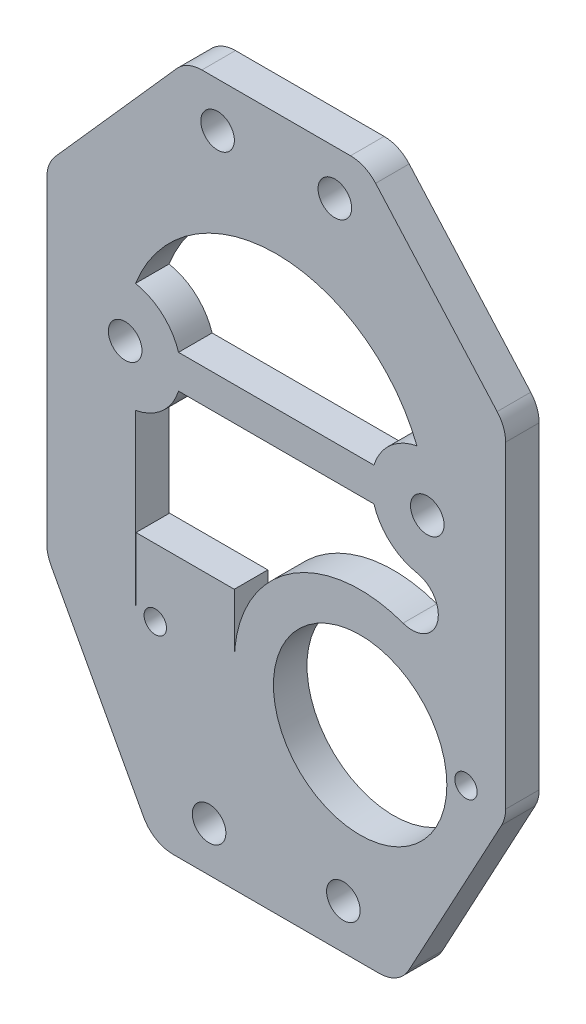
SolidWorks part; units mm, degrees
ref_plane "Front Plane" through (0, 0, 0) normal (0, 0, 1) x (1, 0, 0)
ref_plane "Top Plane" through (0, 0, 0) normal (0, 1, 0) x (1, 0, 0)
ref_plane "Right Plane" through (0, 0, 0) normal (1, 0, 0) x (0, 0, -1)
sketch "Sketch1" plane through (0, 0, 0) normal (0, 0, 1) x (1, 0, 0)
  line L0 (0, 0) -> (0, 62) construction
  line L1 (7.9898, 62) -> (-7.9898, 62)
  line L2 (-7.9898, 62) -> (-20.5, 47.8997)
  line L3 (-20.5, 47.8997) -> (-20.5, 17.5997)
  line L4 (-20.5, 17.5997) -> (-11, 0)
  line L5 (-11, 0) -> (0, 0)
  line L6 (20.5, 17.5997) -> (11, 0)
  line L7 (20.5, 47.8997) -> (20.5, 17.5997)
  line L8 (7.9898, 62) -> (20.5, 47.8997)
  line L9 (7.5, 17.5997) -> (20.5, 17.5997) construction
  line L10 (-13.5, 37.5997) -> (13.5, 37.5997) construction
  line L11 (13.5, 37.5997) -> (11.3388, 28.1745) construction
  line L12 (8.7303, 36.0997) -> (-8.7303, 36.0997)
  line L13 (8.7303, 36.0997) -> (8.7303, 39.0997) construction
  line L14 (8.7303, 39.0997) -> (-8.7303, 39.0997)
  line L15 (-8.7303, 36.0997) -> (-8.7303, 39.0997) construction
  line L16 (8.7303, 36.0997) -> (-8.7303, 39.0997) construction
  line L17 (8.7303, 39.0997) -> (-8.7303, 36.0997) construction
  line L18 (-12.5741, 32.6862) -> (-12.5741, 17.5997)
  line L19 (0, 0) -> (11, 0)
  line L20 (-12.5741, 17.5997) -> (-12.5295, 17.5997)
  line L21 (-12.5295, 17.5997) -> (-12.5295, 23.2536)
  line L22 (-12.5295, 23.2536) -> (-3.75, 23.2536)
  line L23 (-3.75, 23.2536) -> (-3.75, 17.5997)
  circle A0 centre (-6, 4) radius 1.5
  circle A1 centre (-13.5, 37.5997) radius 1.5
  circle A2 centre (-5.2398, 58) radius 1.5
  circle A3 centre (5.2398, 58) radius 1.5
  circle A4 centre (13.5, 37.5997) radius 1.5
  circle A5 centre (6, 4) radius 1.5
  circle A6 centre (7.5, 17.5997) radius 7.75
  circle A7 centre (7.5, 17.5997) radius 11.25 construction
  circle A8 centre (13.5, 37.5997) radius 5 construction
  circle A9 centre (-13.5, 37.5997) radius 5 construction
  arc A10 (-12.5741, 42.5132) -> (12.5741, 42.5132) centre (0, 37.5997) cw
  arc A11 (-12.5741, 42.5132) -> (-8.7303, 39.0997) centre (-13.5, 37.5997) cw
  arc A12 (8.7303, 39.0997) -> (12.5741, 42.5132) centre (13.5, 37.5997) cw
  arc A13 (-8.7303, 36.0997) -> (-12.5741, 32.6862) centre (-13.5, 37.5997) cw
  arc A14 (8.7303, 36.0997) -> (12.5741, 32.6862) centre (13.5, 37.5997) ccw
  arc A15 (12.5741, 32.6862) -> (11.3388, 28.1745) centre (12.1395, 30.3802) cw
  arc A16 (11.3388, 28.1745) -> (-3.75, 17.5997) centre (7.5, 17.5997) ccw
  dimension "D7" = 3
  dimension "D11" = 4
  dimension "D13" = 10.3
  dimension "D14" = 15.5
  dimension "D19" = 13.5
  dimension "D1" = 62
  dimension "D2" = 11
  dimension "D3" = 20
  dimension "D4" = 30.3
  dimension "D5" = 18.85
  dimension "D6" = 20.5
  dimension "D8" = 4
  dimension "D9" = 2.75
  dimension "D10" = 6
  dimension "D12" = 7
  dimension "D15" = 13
  dimension "D20" = 3
  dimension "D16" = 3.5
  dimension "D17" = 3.5
  dimension "D18" = 3.5
extrude "Boss-Extrude1" add sketch "Sketch1" along normal blind 3
fillet "Fillet1" radius 3 8 edges at (-11, 0, 1.5) (-20.5, 17.5997, 1.5) (-20.5, 47.8997, 1.5) (-7.9898, 62, 1.5) (7.9898, 62, 1.5) (20.5, 47.8997, 1.5) (11, 0, 1.5) (20.5, 17.5997, 1.5)
sketch "Sketch2" plane through (0, 0, 3) normal (0, 0, 1) x (1, 0, 0)
  circle A0 centre (16.9601, 18.4104) radius 1
  circle A1 centre (-10.8086, 17.2132) radius 1
  dimension "D1" = 2
  dimension "D2" = 2
extrude "Cut-Extrude1" cut sketch "Sketch2" against normal blind 10
